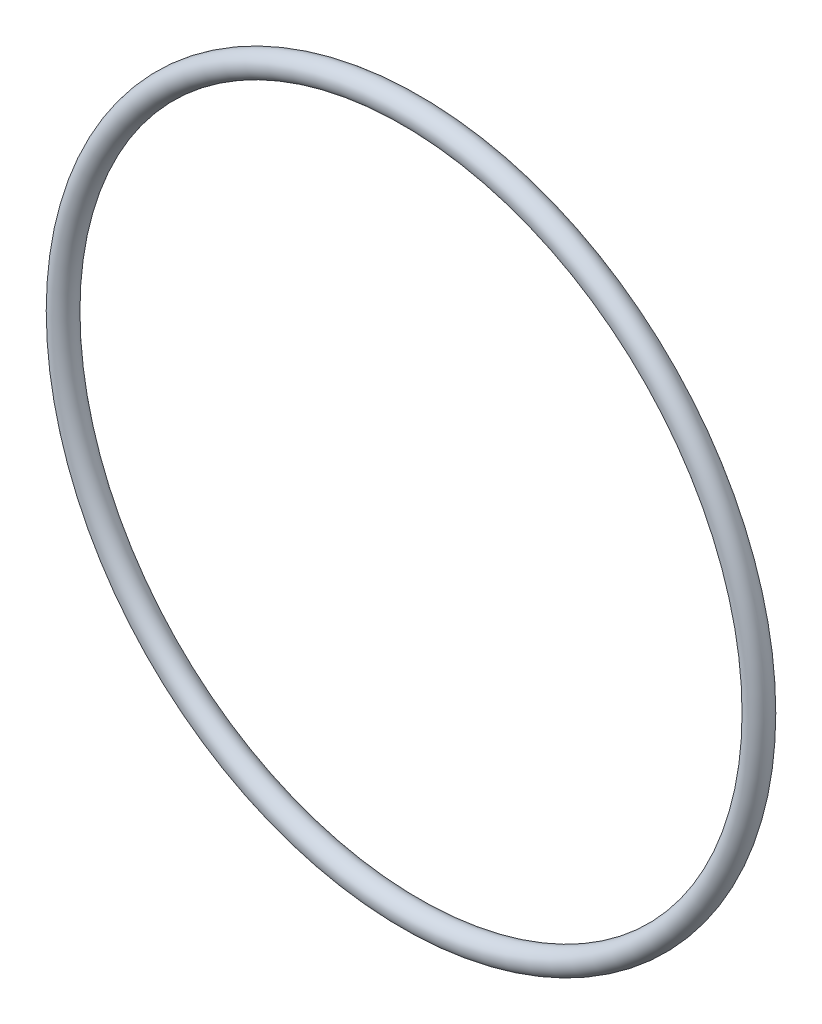
SolidWorks part; units mm, degrees
material "Silicon Rubber"
ref_plane "Front Plane" through (0, 0, 0) normal (0, 0, 1) x (1, 0, 0)
ref_plane "Top Plane" through (0, 0, 0) normal (0, 1, 0) x (1, 0, 0)
ref_plane "Right Plane" through (0, 0, 0) normal (1, 0, 0) x (0, 0, -1)
sketch "Sketch1" plane through (0, 0, 0) normal (0, 0, 1) x (1, 0, 0)
  circle A0 centre (0, 0) radius 44.45
  dimension "D1" = 88.9
sweep "Sweep1" add path "Sketch1" circular profile diameter 3.048 parameters "D3"=3.048
